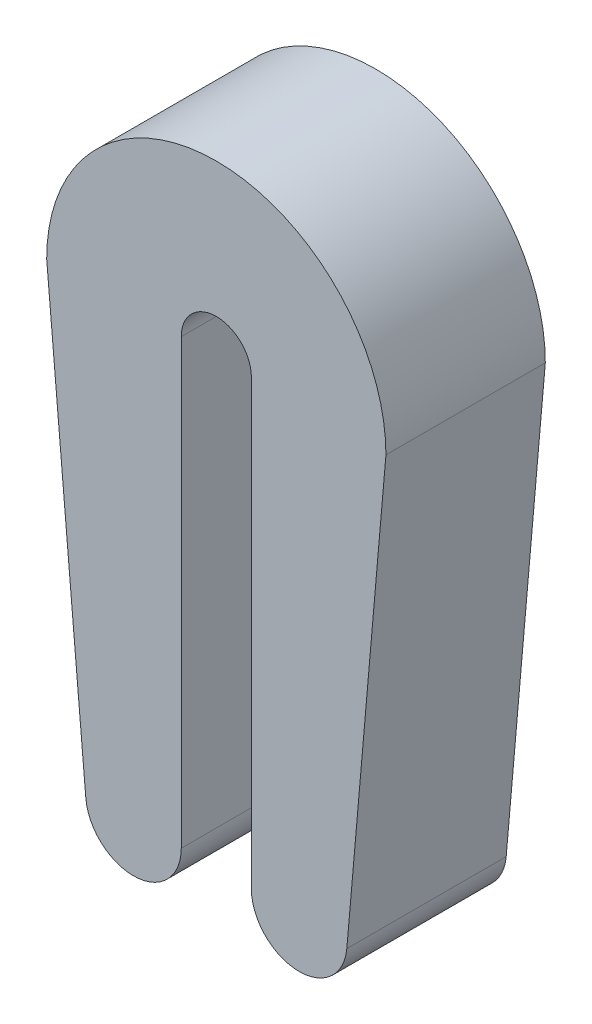
SolidWorks part; units mm, degrees
ref_plane "Front Plane" through (0, 0, 0) normal (0, 0, 1) x (1, 0, 0)
ref_plane "Top Plane" through (0, 0, 0) normal (0, 1, 0) x (1, 0, 0)
ref_plane "Right Plane" through (0, 0, 0) normal (1, 0, 0) x (0, 0, -1)
sketch "Sketch1" plane through (0, 0, 0) normal (0, 0, 1) x (1, 0, 0)
  line L0 (-1.1, 0) -> (-1.1, -13.9)
  line L1 (0, 0) -> (0, 10.0147) construction
  line L2 (0, 0) -> (3.1548, 0) construction
  line L3 (-4.0943, -14.0307) -> (-5.3218, 0)
  line L4 (4.0943, -14.0307) -> (5.3218, 0)
  line L5 (1.1, 0) -> (1.1, -13.9)
  arc A0 (-1.1, 0) -> (1.1, 0) centre (0, 0) cw
  arc A1 (-5.3218, 0) -> (5.3218, 0) centre (0, 0) cw
  arc A2 (-4.0943, -14.0307) -> (-1.1, -13.9) centre (-2.6, -13.9) ccw
  arc A3 (4.0943, -14.0307) -> (1.1, -13.9) centre (2.6, -13.9) cw
  point P7 (0, 1.1)
  point P13 (0, 0)
  dimension "D4" = 1.5
  dimension "D1" = 1.1
  dimension "D2" = 13.9
  dimension "D3" = 5
extrude "Boss-Extrude1" add sketch "Sketch1" along normal blind 5
